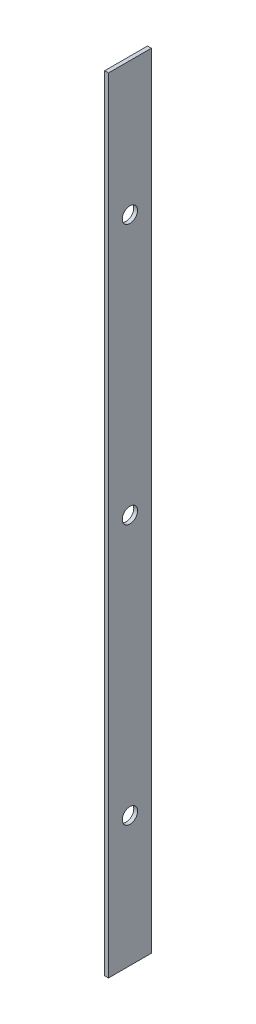
SolidWorks part; units mm, degrees
material "Custom Plastic"
ref_plane "X-Y Datum" through (0, 0, 0) normal (0, 0, 1) x (1, 0, 0)
ref_plane "X-Z Datum" through (0, 0, 0) normal (0, 1, 0) x (1, 0, 0)
ref_plane "Y-Z Datum" through (0, 0, 0) normal (1, 0, 0) x (0, 0, -1)
sketch "Sketch2" plane through (0, 0, 0) normal (1, 0, 0) x (0, 0, -1)
  line L4 (-8.1795, 145.9636) -> (-24.8935, 145.9636)
  line L5 (-8.1795, -160.146) -> (-8.1795, 145.9636)
  line L6 (-24.8935, -160.146) -> (-8.1795, -160.146)
  line L7 (-24.8935, 145.9636) -> (-24.8935, -160.146)
  line L8 (-8.1795, 145.9636) -> (-24.8935, 145.9636)
  line L9 (-8.1795, -160.146) -> (-8.1795, 145.9636)
  line L10 (-24.8935, -160.146) -> (-8.1795, -160.146)
  line L11 (-24.8935, 145.9636) -> (-24.8935, -160.146)
  circle A0 centre (-16.5365, 93.854) radius 3
  circle A1 centre (-16.5365, -7.746) radius 3
  circle A2 centre (-16.5365, -109.346) radius 3
  point P2 (-16.5365, 93.854)
  point P4 (-16.5365, -7.746)
  point P6 (-16.5365, -109.346)
  dimension "D2" = 6
  dimension "D1" = 0
extrude "Boss-Extrude1" add sketch "Sketch2" along normal blind 1.5
